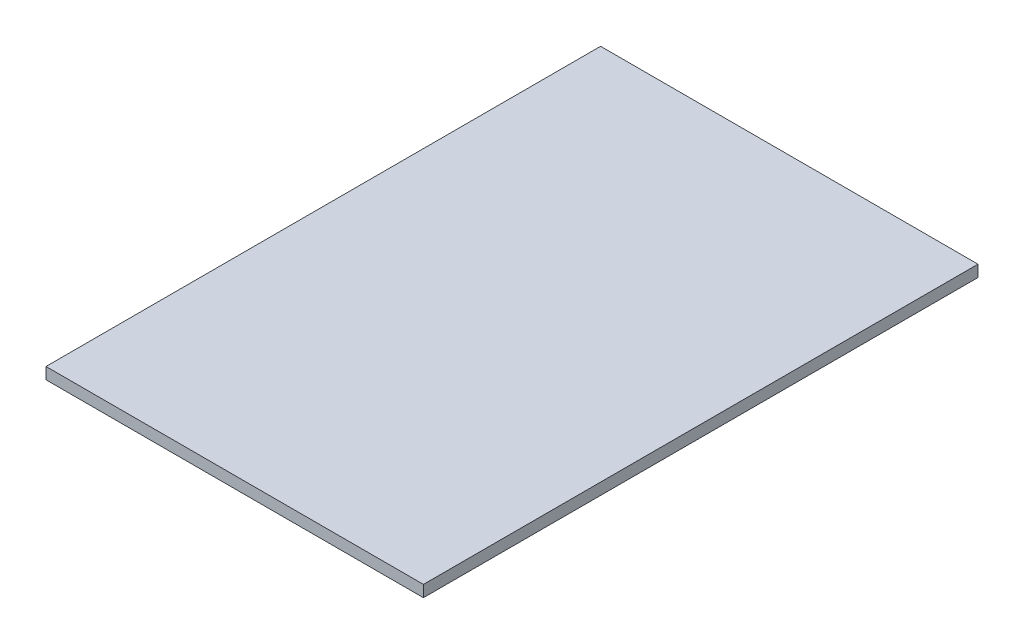
SolidWorks part; units mm, degrees
ref_plane "Front Plane" through (0, 0, 0) normal (0, 0, 1) x (1, 0, 0)
ref_plane "Top Plane" through (0, 0, 0) normal (0, 1, 0) x (1, 0, 0)
ref_plane "Right Plane" through (0, 0, 0) normal (1, 0, 0) x (0, 0, -1)
sketch "Sketch3" plane through (0, 0, 0) normal (0, 1, 0) x (1, 0, 0)
  line L1 (0, 0) -> (49, 0)
  line L2 (0, 0) -> (0, 72)
  line L3 (0, 72) -> (49, 72)
  line L4 (49, 0) -> (49, 72)
  dimension "D1" = 49
  dimension "D2" = 72
extrude "Boss-Extrude1" add sketch "Sketch3" along normal blind 1.5
